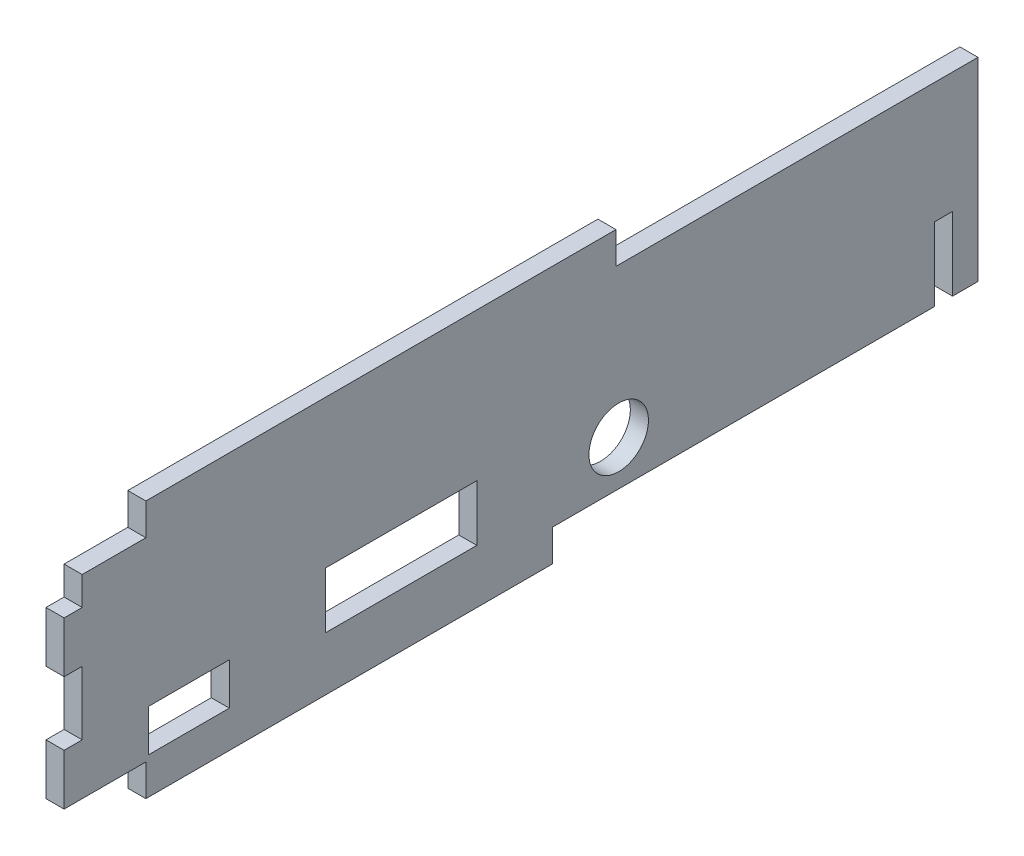
SolidWorks part; units mm, degrees
ref_plane "Front" through (0, 0, 0) normal (0, 0, 1) x (1, 0, 0)
ref_plane "Top" through (0, 0, 0) normal (0, 1, 0) x (1, 0, 0)
ref_plane "Right" through (0, 0, 0) normal (1, 0, 0) x (0, 0, -1)
sketch "Sketch2" plane through (0, 0, 0) normal (1, 0, 0) x (0, 0, -1)
  line L0 (0, 4.7244) -> (84.963, 4.7244) construction
  line L1 (0, 24.0792) -> (84.963, 24.0792)
  line L2 (0, 24.0792) -> (0, 0)
  line L3 (0, 0) -> (84.963, 0)
  line L4 (84.963, 24.0792) -> (84.963, 0)
  line L5 (6.6294, 9.3853) -> (14.6685, 9.3853)
  line L6 (6.6294, 9.3853) -> (6.6294, 5.207)
  line L7 (6.6294, 5.207) -> (14.6685, 5.207)
  line L8 (14.6685, 9.3853) -> (14.6685, 5.207)
  line L9 (24.257, 6.9215) -> (39.3446, 6.9215)
  line L10 (24.257, 6.9215) -> (24.257, 12.5095)
  line L11 (24.257, 12.5095) -> (39.3446, 12.5095)
  line L12 (39.3446, 6.9215) -> (39.3446, 12.5095)
  line L13 (53.486, 12.1412) -> (53.486, 4.7244) construction
  line L14 (6.35, 24.0792) -> (6.35, 27.2542)
  line L15 (6.35, 27.2542) -> (53.213, 27.2542)
  line L16 (84.963, 24.0792) -> (86.7664, 24.0792)
  line L17 (6.35, 4.7244) -> (6.35, 1.5494)
  line L18 (6.35, 1.5494) -> (46.863, 1.5494)
  line L19 (46.863, 1.5494) -> (46.863, 4.7244)
  line L20 (46.863, 4.7244) -> (84.963, 4.7244)
  line L21 (6.35, 4.7244) -> (0, 4.7244)
  line L22 (86.7664, 24.0792) -> (86.7664, 4.7244)
  line L23 (86.7664, 24.0792) -> (89.3064, 24.0792)
  line L24 (89.3064, 24.0792) -> (89.3064, 4.7244)
  line L25 (84.963, 12.0396) -> (86.7664, 12.0396)
  line L26 (86.7664, 4.7244) -> (89.3064, 4.7244)
  line L28 (42.4815, 24.0792) -> (42.4815, -8.3898) construction
  line L29 (-1.8034, 4.7244) -> (0, 4.7244)
  line L30 (-1.8034, 9.8044) -> (-1.8034, 4.7244)
  line L31 (-1.8034, 9.8044) -> (0, 9.8044)
  line L32 (-1.8034, 16.1544) -> (0, 16.1544)
  line L33 (-1.8034, 21.2344) -> (-1.8034, 16.1544)
  line L34 (0, 21.2344) -> (-1.8034, 21.2344)
  line L35 (53.213, 27.2542) -> (53.213, 24.0792)
  circle A0 centre (53.486, 9.1758) radius 2.9655
  dimension "D11" = 5.9309
  dimension "D13" = 11.176
  dimension "D1" = 84.963
  dimension "D2" = 8.0391
  dimension "D3" = 15.0876
  dimension "D4" = 4.6609
  dimension "D5" = 4.1783
  dimension "D6" = 6.6294
  dimension "D7" = 7.7851
  dimension "D8" = 5.588
  dimension "D9" = 9.5885
  dimension "D10" = 4.7244
  dimension "D12" = 7.4168
  dimension "D14" = 19.3548
  dimension "D15" = 6.35
  dimension "D16" = 3.175
  dimension "D17" = 3.175
  dimension "D18" = 38.1
  dimension "D19" = 1.8034
  dimension "D20" = 2.8448
  dimension "D21" = 5.08
  dimension "D22" = 5.08
  dimension "D23" = 31.75
extrude "Boss-Extrude1" add sketch "Sketch2" along normal blind 1.8034
